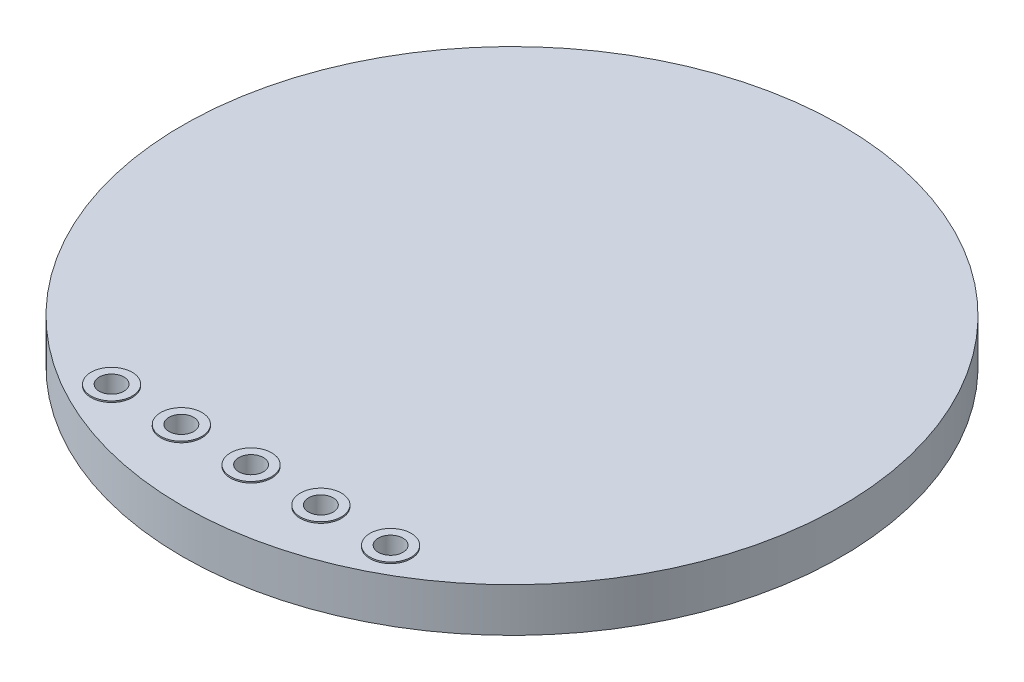
SolidWorks part; units mm, degrees
ref_plane "Piano frontale" through (0, 0, 0) normal (0, 0, 1) x (1, 0, 0)
ref_plane "Piano superiore" through (0, 0, 0) normal (0, 1, 0) x (1, 0, 0)
ref_plane "Piano destro" through (0, 0, 0) normal (1, 0, 0) x (0, 0, -1)
sketch "Schizzo1" plane through (0, 0, 0) normal (0, 1, 0) x (1, 0, 0)
  circle A0 centre (0, 0) radius 12
  dimension "D1" = 24
extrude "Estrusione-Estrusione1" add sketch "Schizzo1" along normal mid plane 1.6
sketch "Schizzo2" plane through (0, 0.8, 0) normal (0, 1, 0) x (1, 0, 0)
  line L0 (0, 9.343) -> (0, -13.3122) construction
  line L1 (-10.2238, -9.5) -> (10.2169, -9.5) construction
  circle A0 centre (0, -9.5) radius 0.45
  circle A1 centre (2.54, -9.5) radius 0.45
  circle A2 centre (5.08, -9.5) radius 0.45
  circle A3 centre (-2.54, -9.5) radius 0.45
  circle A4 centre (-5.08, -9.5) radius 0.45
  dimension "D3" = 0.9
  dimension "D4" = 9.5
  dimension "D1" = 3
  dimension "D2" = 3
extrude "Taglio-Estrusione1" cut sketch "Schizzo2" against normal through all
sketch "Schizzo3" plane through (0, 0.8, 0) normal (0, 1, 0) x (1, 0, 0)
  circle A0 centre (-5.08, -9.5) radius 0.45 construction
  circle A1 centre (-2.54, -9.5) radius 0.45 construction
  circle A2 centre (0, -9.5) radius 0.45 construction
  circle A3 centre (2.54, -9.5) radius 0.45 construction
  circle A4 centre (5.08, -9.5) radius 0.45 construction
  circle A5 centre (-5.08, -9.5) radius 0.45
  circle A6 centre (-2.54, -9.5) radius 0.45
  circle A7 centre (0, -9.5) radius 0.45
  circle A8 centre (2.54, -9.5) radius 0.45
  circle A9 centre (5.08, -9.5) radius 0.45
  circle A10 centre (-5.08, -9.5) radius 0.75
  circle A11 centre (-2.54, -9.5) radius 0.75
  circle A12 centre (0, -9.5) radius 0.75
  circle A13 centre (2.54, -9.5) radius 0.75
  circle A14 centre (5.08, -9.5) radius 0.75
  dimension "D1" = 0.3
extrude "Estrusione-Estrusione2" add sketch "Schizzo3" along normal mid plane 0.1
mirror "Specchia1" about plane through (0, 0, 0) normal (0, 1, 0) of "Estrusione-Estrusione2"
